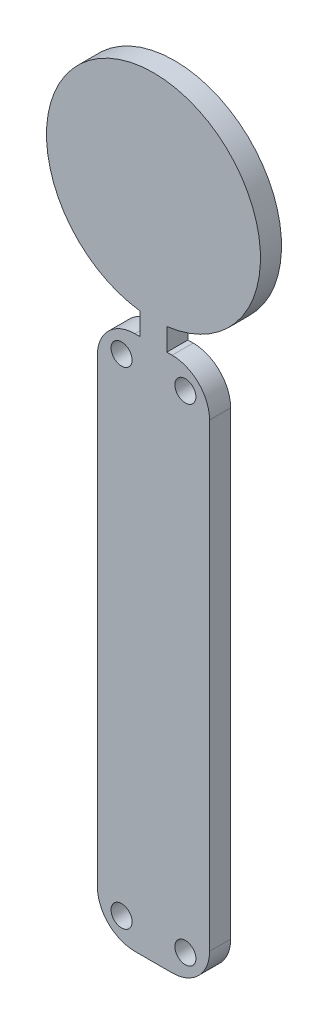
SolidWorks part; units mm, degrees
ref_plane "Front Plane" through (0, 0, 0) normal (0, 0, 1) x (1, 0, 0)
ref_plane "Top Plane" through (0, 0, 0) normal (0, 1, 0) x (1, 0, 0)
ref_plane "Right Plane" through (0, 0, 0) normal (1, 0, 0) x (0, 0, -1)
sketch "Sketch2" plane through (0, 0, 0) normal (0, 0, 1) x (1, 0, 0)
  line L14 (-7.0745, 38.4443) -> (-7.0745, 37.9163)
  line L15 (-7.0745, 37.9163) -> (-7.2001, 37.9163)
  line L16 (-8.0891, 37.0273) -> (-8.0891, 26.1053)
  line L17 (-7.2001, 25.2163) -> (-6.3138, 25.2163)
  line L18 (-5.4248, 26.1053) -> (-5.4248, 37.0273)
  line L19 (-6.3138, 37.9163) -> (-6.4395, 37.9163)
  line L20 (-6.4395, 37.9163) -> (-6.4395, 38.4443)
  arc A10 (-6.4395, 38.4443) -> (-7.0745, 38.4443) centre (-6.757, 40.9643) ccw
  arc A11 (-7.2001, 37.9163) -> (-8.0891, 37.0273) centre (-7.2001, 37.0273) ccw
  arc A12 (-8.0891, 26.1053) -> (-7.2001, 25.2163) centre (-7.2001, 26.1053) ccw
  arc A13 (-6.3138, 25.2163) -> (-5.4248, 26.1053) centre (-6.3138, 26.1053) ccw
  arc A14 (-5.4248, 37.0273) -> (-6.3138, 37.9163) centre (-6.3138, 37.0273) ccw
extrude "Boss-Extrude1" add sketch "Sketch2" along normal mid plane 0.5
sketch "Sketch4" plane through (0, 0, 0.25) normal (0, 0, 1) x (1, 0, 0)
  circle A2 centre (-7.5144, 25.791) radius 0.25
  circle A4 centre (-5.9995, 25.791) radius 0.25
  circle A6 centre (-7.5144, 37.3416) radius 0.25
  circle A8 centre (-5.9995, 37.3416) radius 0.25
  dimension "D1" = 0.5
extrude "Cut-Extrude1" cut sketch "Sketch4" against normal blind 9.5
